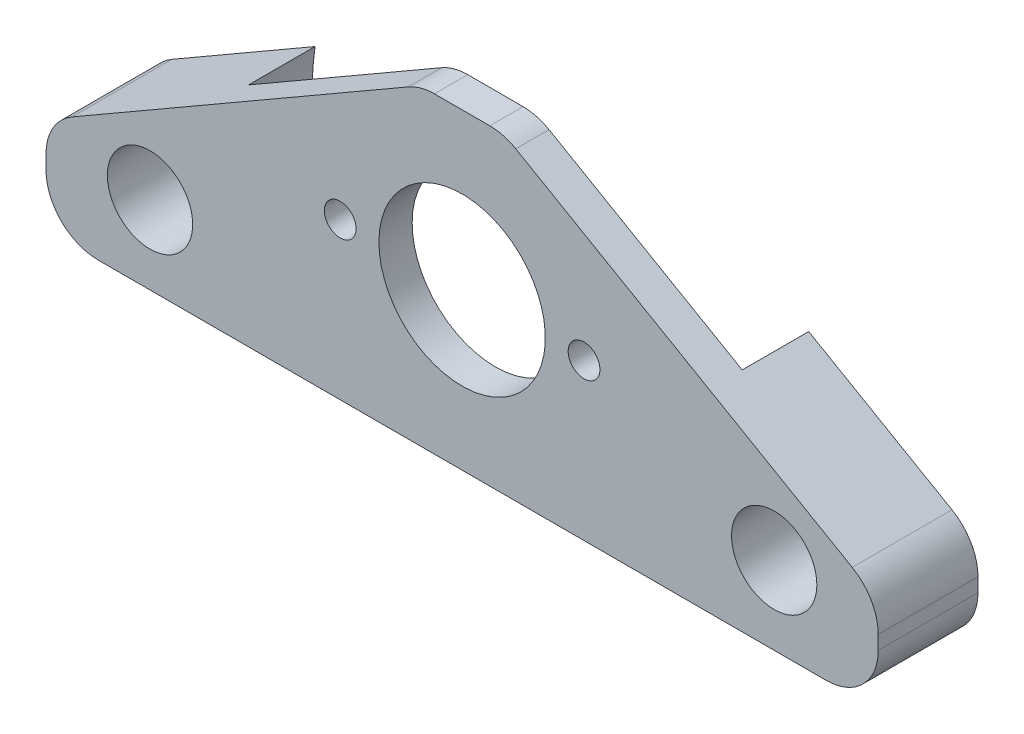
SolidWorks part; units mm, degrees
material "ABS PC"
ref_plane "Front" through (0, 0, 0) normal (0, 0, 1) x (1, 0, 0)
ref_plane "Top" through (0, 0, 0) normal (0, 1, 0) x (1, 0, 0)
ref_plane "Right" through (0, 0, 0) normal (1, 0, 0) x (0, 0, -1)
sketch "Sketch1" plane through (0, 0, 0) normal (0, 0, 1) x (1, 0, 0)
  line L0 (0, 0) -> (0, 19.05) construction
  line L1 (0, 19.05) -> (0, 0)
  line L12 (25.4, 5.8518) -> (2.54, 19.05)
  line L13 (25.4, 0) -> (25.4, 5.8518)
  line L14 (0, 0) -> (25.4, 0)
  line L17 (2.54, 19.05) -> (0, 19.05)
  dimension "D3" = 25.4
  dimension "D2" = 5.8518
  dimension "D1" = 30
  dimension "D5" = 19.05
extrude "Extrude1" add sketch "Sketch1" against normal blind 2.03 from offset 1 offset against normal yes
sketch "Sketch2" plane through (0, 0, -3.03) normal (0, 0, -1) x (-1, 0, 0)
  line L3 (-25.4, 0) -> (-25.4, 5.8518) construction
  line L4 (-25.4, 5.8518) -> (-2.54, 19.05) construction
  line L5 (0, 0) -> (-25.4, 0) construction
  line L6 (-11.8967, 0) -> (-25.4, 0)
  line L8 (-25.4, 0) -> (-25.4, 5.8518)
  line L9 (-25.4, 5.8518) -> (-15.0665, 11.8178)
  arc A2 (-15.0665, 11.8178) -> (-11.8967, 0) centre (0, 9.525) ccw
  dimension "D2" = 15.24
  dimension "D3" = 11.8967
  dimension "D4" = 15.0665
extrude "Extrude2" add sketch "Sketch2" along normal blind 4.06
sketch "Sketch4" plane through (0, 0, -7.09) normal (0, 0, -1) x (-1, 0, 0)
  line L0 (0, 19.05) -> (0, 0) construction
  line L1 (0, 0) -> (0, 21.9187) construction
  circle A0 centre (0, 9.525) radius 5.08
  circle A3 centre (-19.05, 4.7625) radius 2.6035
  circle A4 centre (-7.4422, 9.525) radius 0.9703
  dimension "D1" = 10.16
  dimension "D2" = 1.9406
  dimension "D3" = 5.207
  dimension "D4" = 7.4422
  dimension "D5" = 38.1
  dimension "D6" = 4.7625
extrude "Extrude3" cut sketch "Sketch4" against normal through all
fillet "Fillet1" radius 3.175 3 edges at (2.54, 19.05, -2.015) (25.4, 0, -4.045) (25.4, 5.8518, -4.045)
mirror "Mirror1" about plane through (0, 19.05, -3.03) normal (-1, 0, 0) of bodies 106
